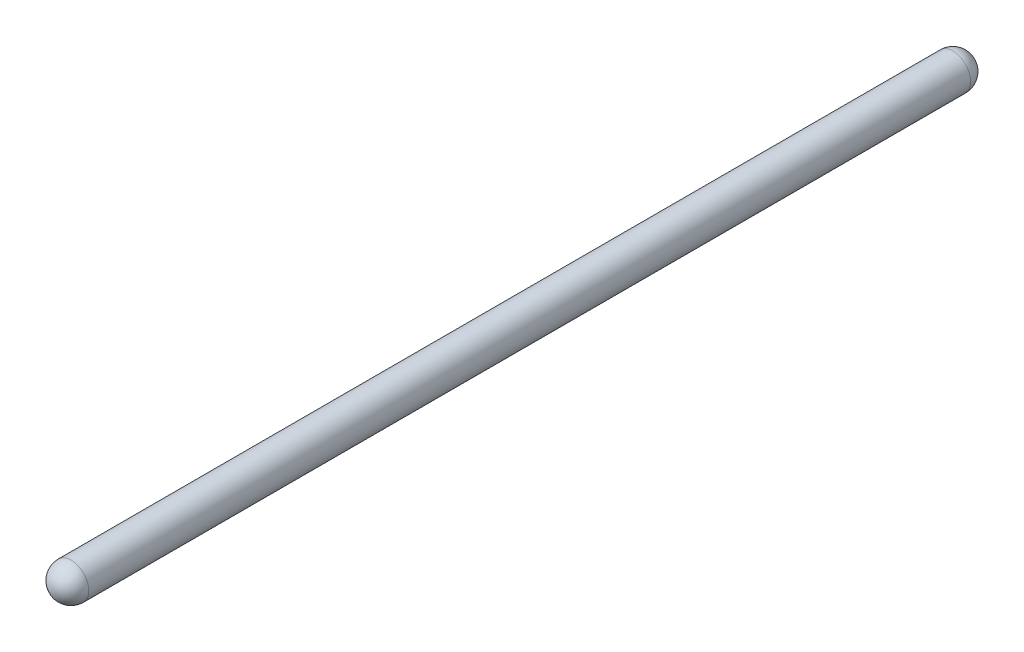
SolidWorks part; units mm, degrees
ref_plane "Спереди" through (0, 0, 0) normal (0, 0, 1) x (1, 0, 0)
ref_plane "Сверху" through (0, 0, 0) normal (0, 1, 0) x (1, 0, 0)
ref_plane "Справа" through (0, 0, 0) normal (1, 0, 0) x (0, 0, -1)
sketch "Эскиз1" plane through (0, 0, 0) normal (0, 0, 1) x (1, 0, 0)
  circle A0 centre (0, 0) radius 6
extrude "Бобышка-Вытянуть1" add sketch "Эскиз1" along normal blind 310
fillet "Скругление3" radius 6 1 edges at (6, 0, 310)
fillet "Скругление4" radius 6 1 edges at (6, 0, 0)
